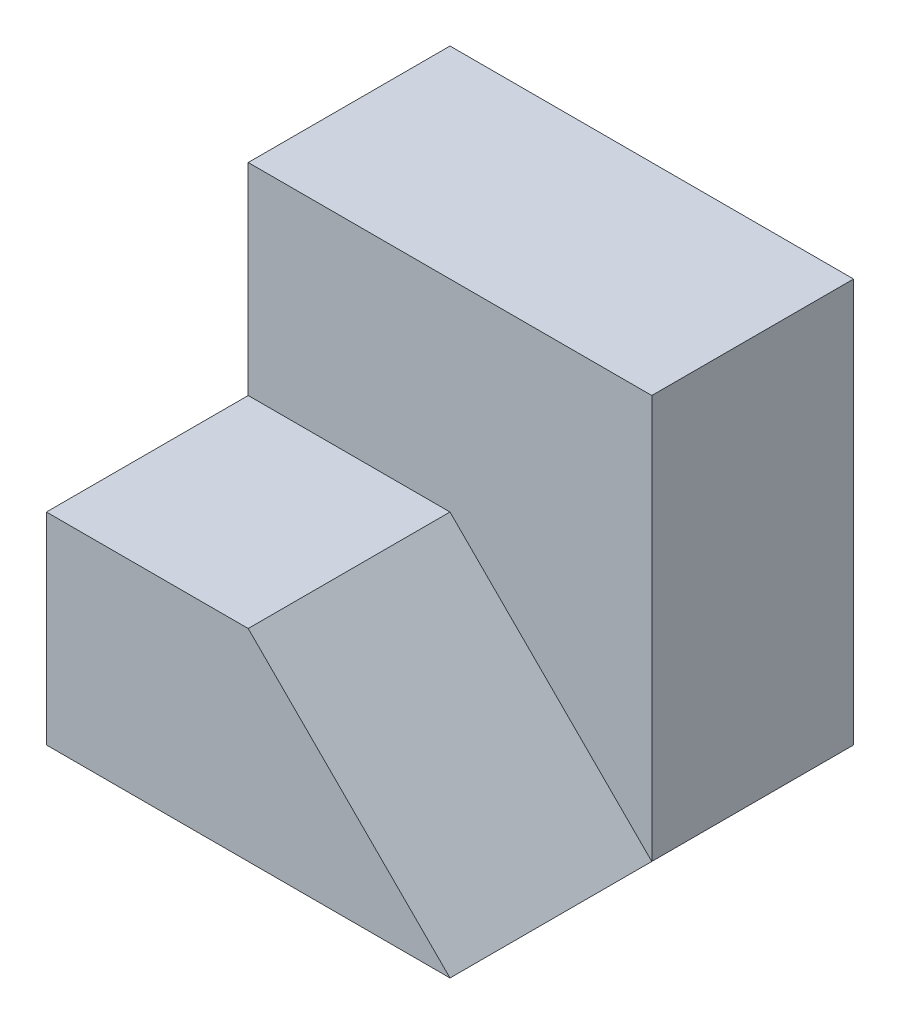
SolidWorks part; units mm, degrees
ref_plane "Plano frontal" through (0, 0, 0) normal (0, 0, 1) x (1, 0, 0)
ref_plane "Plano superior" through (0, 0, 0) normal (0, 1, 0) x (1, 0, 0)
ref_plane "Plano direito" through (0, 0, 0) normal (1, 0, 0) x (0, 0, -1)
sketch "Esboço1" plane through (0, 0, 0) normal (0, 0, 1) x (1, 0, 0)
  line L0 (0, 0) -> (60, 0)
  line L1 (0, 0) -> (0, 30)
  line L2 (0, 30) -> (30, 30)
  line L3 (30, 30) -> (60, 0)
  dimension "D1" = 30
  dimension "D2" = 30
  dimension "D3" = 60
extrude "Ressalto-extrusão1" add sketch "Esboço1" along normal blind 30
sketch "Esboço2" plane through (0, 0, 0) normal (0, 0, -1) x (-1, 0, 0)
  line L1 (-60, 0) -> (0, 0)
  line L2 (-60, 0) -> (-60, 60)
  line L3 (-60, 60) -> (0, 60)
  line L4 (0, 0) -> (0, 60)
  dimension "D1" = 60
  dimension "D2" = 60
extrude "Ressalto-extrusão2" add sketch "Esboço2" along normal blind 30
